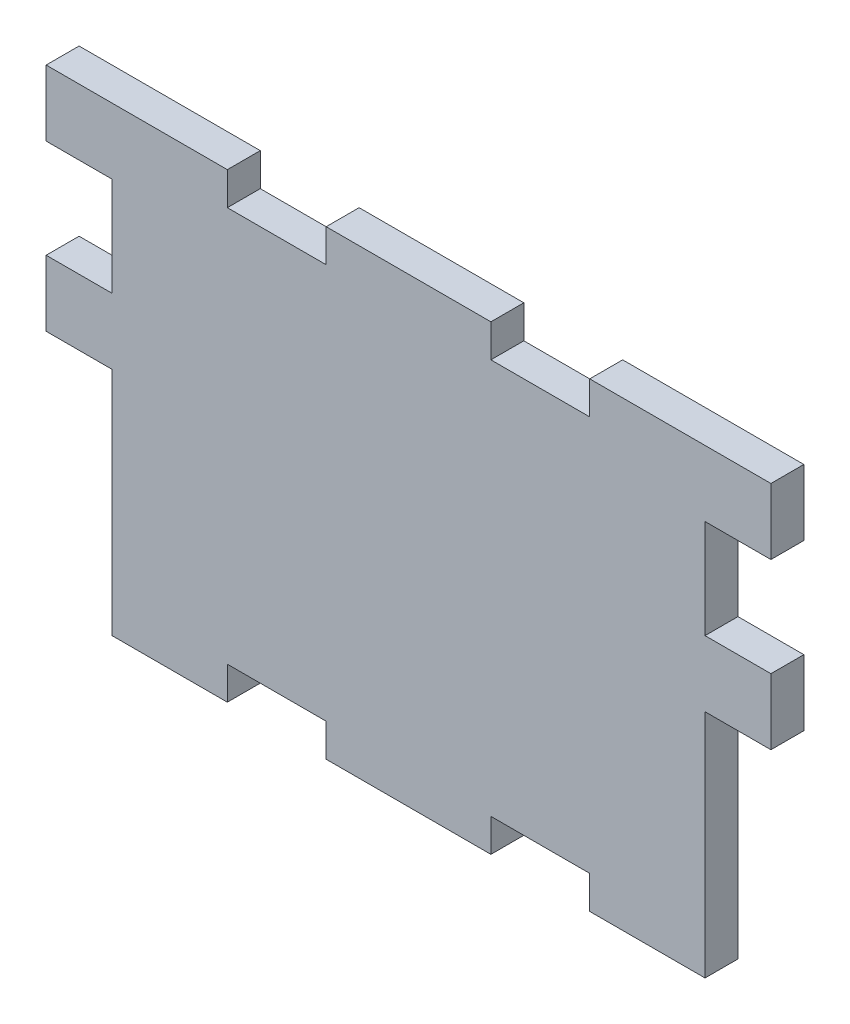
SolidWorks part; units mm, degrees
ref_plane "Plan de face" through (0, 0, 0) normal (0, 0, 1) x (1, 0, 0)
ref_plane "Plan de dessus" through (0, 0, 0) normal (0, 1, 0) x (1, 0, 0)
ref_plane "Plan de droite" through (0, 0, 0) normal (1, 0, 0) x (0, 0, -1)
sketch "Esquisse1" plane through (0, 0, 0) normal (0, 0, 1) x (1, 0, 0)
  line L1 (-55, 35) -> (55, 35)
  line L2 (-55, 35) -> (-55, -35)
  line L3 (-55, -35) -> (55, -35)
  line L4 (55, 35) -> (55, -35)
  line L5 (-55, 35) -> (55, -35) construction
  line L6 (-55, -35) -> (55, 35) construction
  point P0 (0, 0)
  dimension "D1" = 70
  dimension "D2" = 110
extrude "Boss.-Extru.1" add sketch "Esquisse1" along normal blind 5
sketch "Esquisse6" plane through (0, 0, 0) normal (0, 0, -1) x (-1, 0, 0)
  line L0 (-55, 35) -> (55, 35) construction
  line L1 (-55, -35) -> (-45, -35)
  line L2 (-55, -35) -> (-55, 0)
  line L3 (-55, 0) -> (-45, 0)
  line L4 (-45, -35) -> (-45, 0)
  line L5 (55, 35) -> (55, -35) construction
  line L6 (55, -35) -> (45, -35)
  line L7 (55, -35) -> (55, 0)
  line L8 (55, 0) -> (45, 0)
  line L9 (45, -35) -> (45, 0)
  line L10 (-55, 25) -> (-45, 25)
  line L11 (-55, 25) -> (-55, 10)
  line L12 (-55, 10) -> (-45, 10)
  line L13 (-45, 25) -> (-45, 10)
  line L14 (55, 25) -> (45, 25)
  line L15 (55, 25) -> (55, 10)
  line L16 (55, 10) -> (45, 10)
  line L17 (45, 25) -> (45, 10)
  line L18 (-55, -35) -> (-55, 35) construction
  line L19 (55, -35) -> (-55, -35) construction
  line L20 (-27.5, 35) -> (-12.5, 35)
  line L21 (-27.5, 35) -> (-27.5, 30)
  line L22 (-27.5, 30) -> (-12.5, 30)
  line L23 (-12.5, 35) -> (-12.5, 30)
  line L24 (12.5, 35) -> (27.5, 35)
  line L25 (12.5, 35) -> (12.5, 30)
  line L26 (12.5, 30) -> (27.5, 30)
  line L27 (27.5, 35) -> (27.5, 30)
  line L28 (-27.5, -35) -> (-12.5, -35)
  line L29 (-27.5, -35) -> (-27.5, -30)
  line L30 (-27.5, -30) -> (-12.5, -30)
  line L31 (-12.5, -35) -> (-12.5, -30)
  line L33 (12.5, -35) -> (27.5, -35)
  line L34 (12.5, -35) -> (12.5, -30)
  line L35 (12.5, -30) -> (27.5, -30)
  line L36 (27.5, -35) -> (27.5, -30)
  dimension "D1" = 35
  dimension "D2" = 10
  dimension "D3" = 10
  dimension "D4" = 35
  dimension "D5" = 15
  dimension "D6" = 10
  dimension "D7" = 15
  dimension "D8" = 10
  dimension "D9" = 10
  dimension "D10" = 10
  dimension "D11" = 5
  dimension "D12" = 5
  dimension "D13" = 15
  dimension "D14" = 15
  dimension "D15" = 25
  dimension "D16" = 27.5
extrude "Enlèv. mat.-Extru.2" cut sketch "Esquisse6" against normal blind 5
